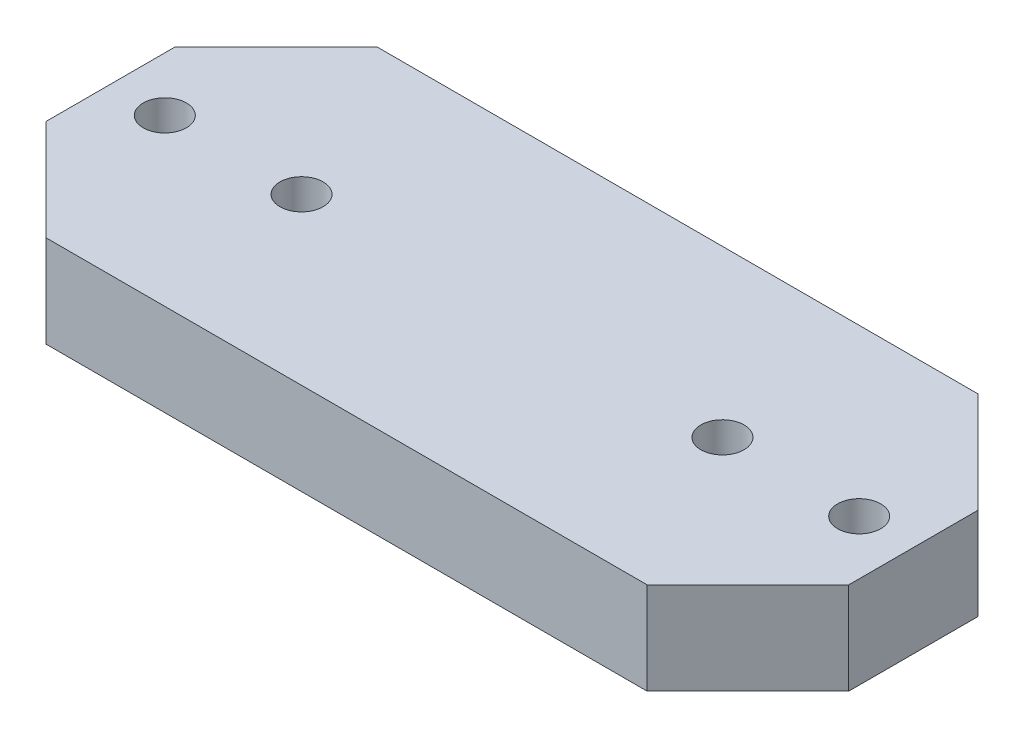
SolidWorks part; units mm, degrees
ref_plane "Front Plane" through (0, 0, 0) normal (0, 0, 1) x (1, 0, 0)
ref_plane "Top Plane" through (0, 0, 0) normal (0, 1, 0) x (1, 0, 0)
ref_plane "Right Plane" through (0, 0, 0) normal (1, 0, 0) x (0, 0, -1)
sketch "Sketch1" plane through (0, 0, 0) normal (0, 1, 0) x (1, 0, 0)
  line L0 (84.3659, 17.6585) -> (93.7763, 17.6585) construction
  line L1 (61.1827, 7.1651) -> (51.6092, 7.1651) construction
  line L2 (89.0711, -4.3283) -> (89.0711, -14.2477) construction
  line L3 (93.7763, -3.3283) -> (106.2976, 3.2433) construction
  line L4 (93.7763, 17.6585) -> (106.2976, 11.0869) construction
  line L5 (109.9595, 18.6585) -> (116.9595, 11.6585)
  line L6 (84.3659, -3.3283) -> (93.7763, -3.3283) construction
  line L7 (68.1827, 18.6585) -> (61.1827, 11.6585)
  line L8 (84.3659, 17.6585) -> (71.8446, 11.0869) construction
  line L9 (84.3659, -3.3283) -> (71.8446, 3.2433) construction
  line L10 (116.9595, 2.6717) -> (116.9595, 11.6585)
  line L11 (109.9595, 18.6585) -> (68.1827, 18.6585)
  line L12 (61.1827, 2.6717) -> (61.1827, 11.6585)
  line L13 (68.1827, -4.3283) -> (61.1827, 2.6717)
  line L14 (109.9595, -4.3283) -> (116.9595, 2.6717)
  line L17 (109.9595, -4.3283) -> (68.1827, -4.3283)
  circle A0 centre (74.4461, 7.1651) radius 1.5
  arc A1 (106.2976, 11.0869) -> (106.2976, 3.2433) centre (103.1961, 7.1651) cw construction
  circle A5 centre (113.1961, 7.1651) radius 1.5
  circle A6 centre (89.0711, 7.1651) radius 4 construction
  circle A7 centre (103.6961, 7.1651) radius 1.5
  arc A10 (71.8446, 11.0869) -> (71.8446, 3.2433) centre (74.9461, 7.1651) ccw construction
  circle A22 centre (64.9461, 7.1651) radius 1.5
  point P12 (89.0711, -3.3283)
  point P13 (89.0711, 17.6585)
  dimension "D2" = 3
extrude "Boss-Extrude1" add sketch "Sketch1" along normal blind 6.4
